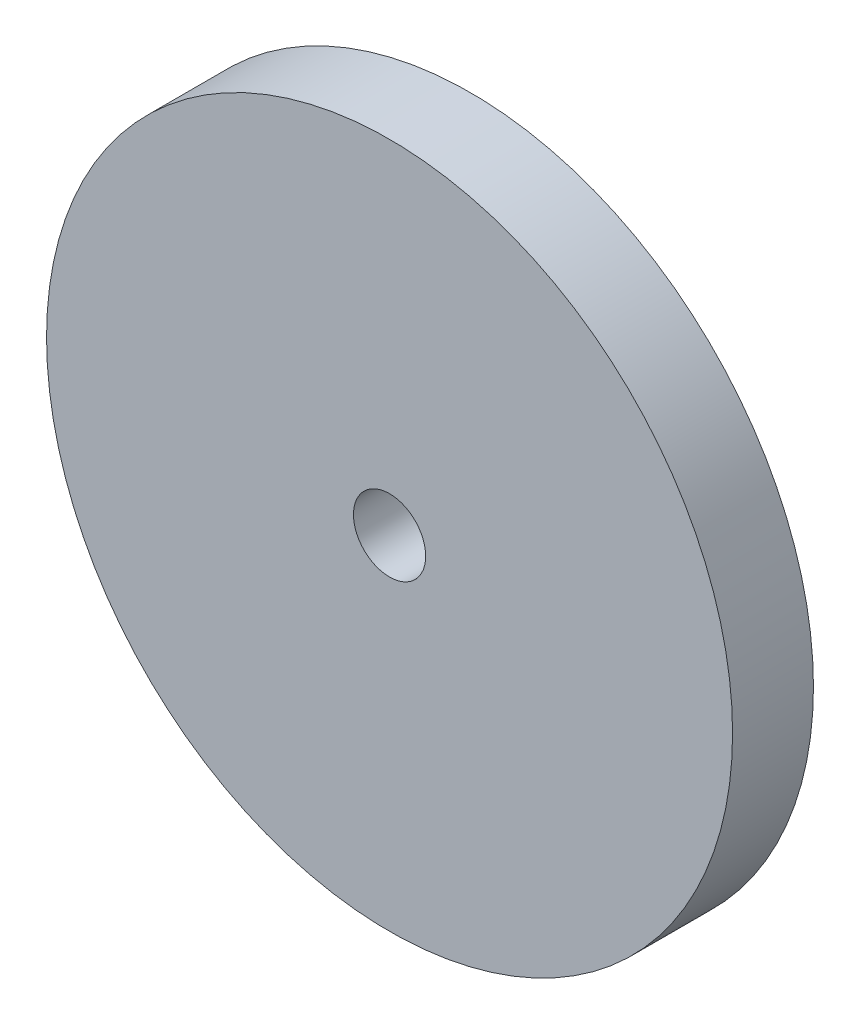
SolidWorks part; units mm, degrees
ref_plane "Front" through (0, 0, 0) normal (0, 0, 1) x (1, 0, 0)
ref_plane "Top" through (0, 0, 0) normal (0, 1, 0) x (1, 0, 0)
ref_plane "Right" through (0, 0, 0) normal (1, 0, 0) x (0, 0, -1)
sketch "Sketch1" plane through (0, 0, 0) normal (0, 0, 1) x (1, 0, 0)
  circle A0 centre (0, 0) radius 30.1625
  dimension "D1" = 60.325
extrude "Boss-Extrude1" add sketch "Sketch1" along normal mid plane 7.112
sketch "Sketch2" plane through (0, 0, 3.556) normal (0, 0, 1) x (1, 0, 0)
  point P0 (0, 0)
hole_wizard "1/4 (0.25) Diameter Hole1" positions "Sketch3" profile "Sketch4" hole size "1/4" standard "ANSI Inch" end condition through all
sketch "Sketch3" plane through (0, 0, 3.556) normal (0, 0, 1) x (1, 0, 0)
  point P0 (0, 0)
sketch "Sketch4" plane through (0, 0, 3.556) normal (1, 0, 0) x (0, -1, 0)
  line L0 (0, 0) -> (0, 7.112)
  line L1 (0, 7.112) -> (3.175, 7.112)
  line L2 (3.175, 7.112) -> (3.175, 0)
  line L5 (3.175, 0) -> (0, 0)
  line L11 (0, -6.35) -> (0, 107.95) construction
  dimension "Thru Hole Dia." = 6.35
  dimension "Thru Hole Depth" = 7.112
